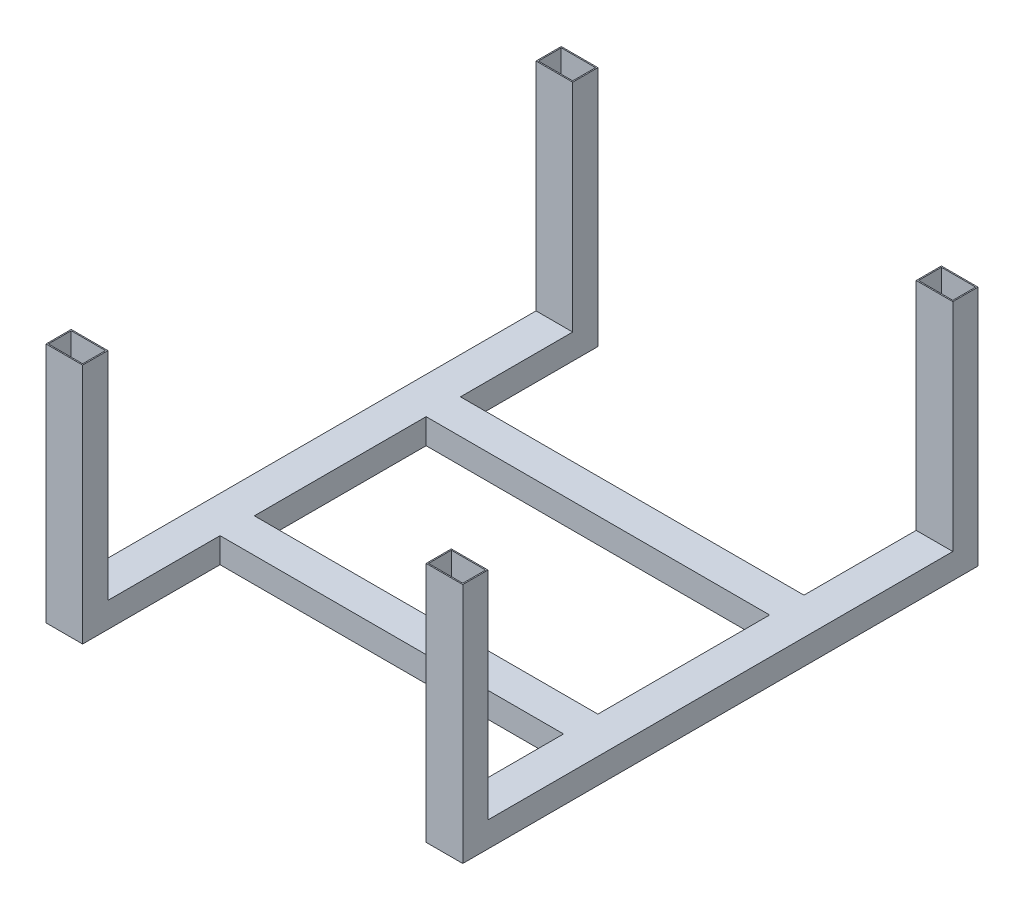
SolidWorks part; units mm, degrees
material "Malleable Cast Iron"
ref_plane "Front Plane" through (0, 0, 0) normal (0, 0, 1) x (1, 0, 0)
ref_plane "Top Plane" through (0, 0, 0) normal (0, 1, 0) x (1, 0, 0)
ref_plane "Right Plane" through (0, 0, 0) normal (1, 0, 0) x (0, 0, -1)
sketch "Sketch1" plane through (0, 0, 0) normal (0, 1, 0) x (1, 0, 0)
  line L1 (-15, -10) -> (15, -10)
  line L2 (-15, -10) -> (-15, 10)
  line L3 (-15, 10) -> (15, 10)
  line L4 (15, -10) -> (15, 10)
  line L5 (-15, -10) -> (15, 10) construction
  line L6 (-15, 10) -> (15, -10) construction
  point P0 (0, 0)
  dimension "D1" = 30
  dimension "D2" = 20
sketch "Sketch2" plane through (0, 0, 0) normal (1, 0, 0) x (0, 0, -1)
  line L0 (0, 0) -> (0, -200)
  line L1 (0, -200) -> (428, -200)
  line L2 (428, -200) -> (428, 0)
  dimension "D1" = 200
  dimension "D2" = 428
  dimension "D3" = 200
sweep "Sweep-Thin1" add profiles "Sketch1" path "Sketch2" parameters "D1"=1
sketch "Sketch3" plane through (16, 0, 0) normal (1, 0, 0) x (0, 0, -1)
  line L0 (11, -189) -> (417, -189) construction
  line L1 (109, -189) -> (139, -189)
  line L2 (109, -189) -> (109, -211)
  line L3 (109, -211) -> (139, -211)
  line L4 (139, -189) -> (139, -211)
  line L5 (-11, -211) -> (439, -211) construction
  line L7 (289, -189) -> (319, -189)
  line L8 (289, -189) -> (289, -211)
  line L9 (289, -211) -> (319, -211)
  line L10 (319, -189) -> (319, -211)
  line L11 (-11, 0) -> (-11, -211) construction
  dimension "D1" = 30
  dimension "D2" = 30
  dimension "D3" = 150
  dimension "D4" = 120
extrude "Extrude-Thin1" add sketch "Sketch3" along normal blind 150 thin
ref_plane "Plane2" through (166, 0, 0) normal (1, 0, 0) x (0, 0, -1)
mirror "Mirror9" about plane through (166, 0, 0) normal (1, 0, 0) of "Extrude-Thin1"
mirror "Mirror10" about plane through (166, 0, 0) normal (1, 0, 0) of "Sweep-Thin1"
